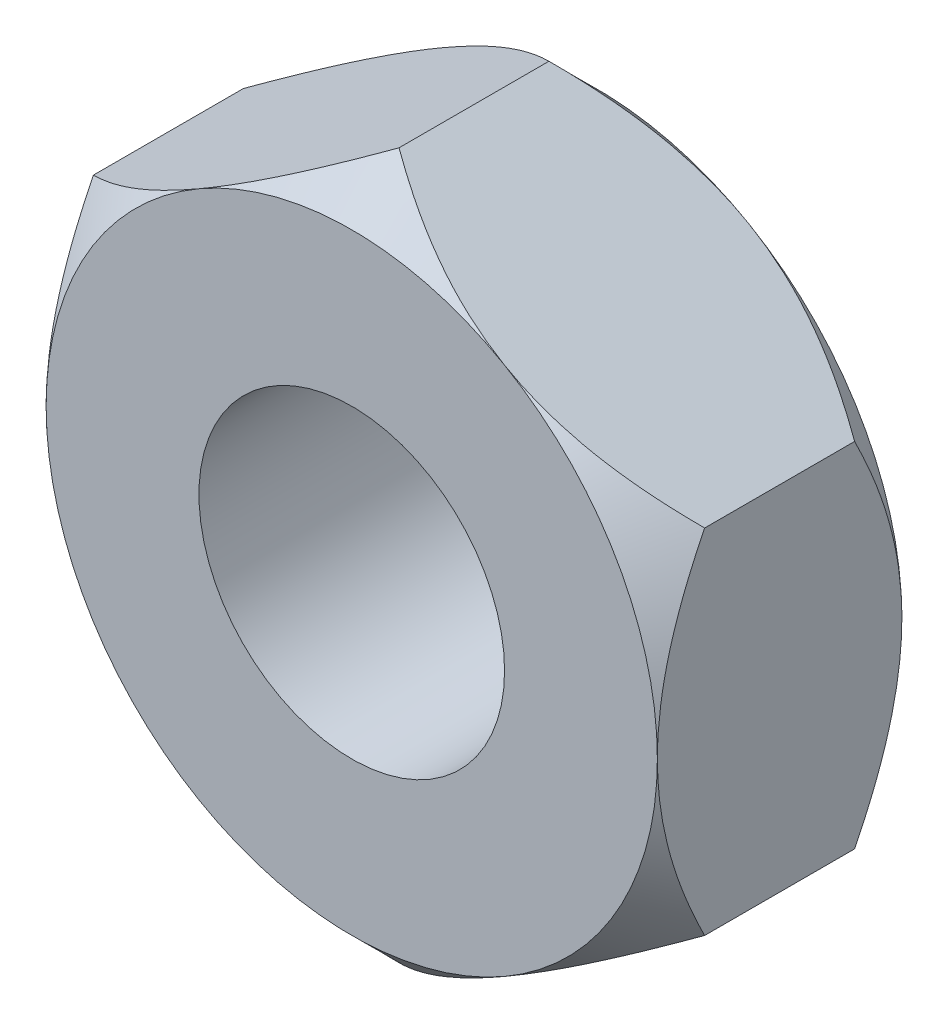
SolidWorks part; units mm, degrees
material "3.0205 (EN-AW 1200)"
ref_plane "Plano frontal" through (0, 0, 0) normal (0, 0, 1) x (1, 0, 0)
ref_plane "Plano superior" through (0, 0, 0) normal (0, 1, 0) x (1, 0, 0)
ref_plane "Plano direito" through (0, 0, 0) normal (1, 0, 0) x (0, 0, -1)
sketch "Esboço1" plane through (0, 0, 0) normal (0, 0, 1) x (1, 0, 0)
  line L1 (-2.5, 1.4434) -> (-2.5, -1.4434)
  line L2 (-2.5, -1.4434) -> (0, -2.8868)
  line L3 (0, -2.8868) -> (2.5, -1.4434)
  line L4 (2.5, -1.4434) -> (2.5, 1.4434)
  line L5 (2.5, 1.4434) -> (0, 2.8868)
  line L6 (0, 2.8868) -> (-2.5, 1.4434)
  circle A0 centre (0, 0) radius 2.5 construction
  circle A1 centre (0, 0) radius 1.25
  dimension "D" = 2.5
  dimension "SW" = 5
extrude "H" add sketch "Esboço1" along normal blind 2 contours L6 L1 L2 L3 L4 L5 | A1
sketch "Esboço2" plane through (0, 0, 2) normal (0, 0, 1) x (1, 0, 0)
  line L0 (0, 2.8868) -> (-2.5, 1.4434) construction
  circle A0 centre (0, 0) radius 2.5
extrude "Corte-extrusão1" cut sketch "Esboço2" against normal blind 2 draft 45 flip side to cut
sketch "Esboço3" plane through (0, 0, 0) normal (0, 0, -1) x (-1, 0, 0)
  line L0 (2.5, 1.4434) -> (1.25, 2.1651) construction
  circle A0 centre (0, 0) radius 2.5
extrude "Corte-extrusão2" cut sketch "Esboço3" against normal blind 2 draft 45 flip side to cut
